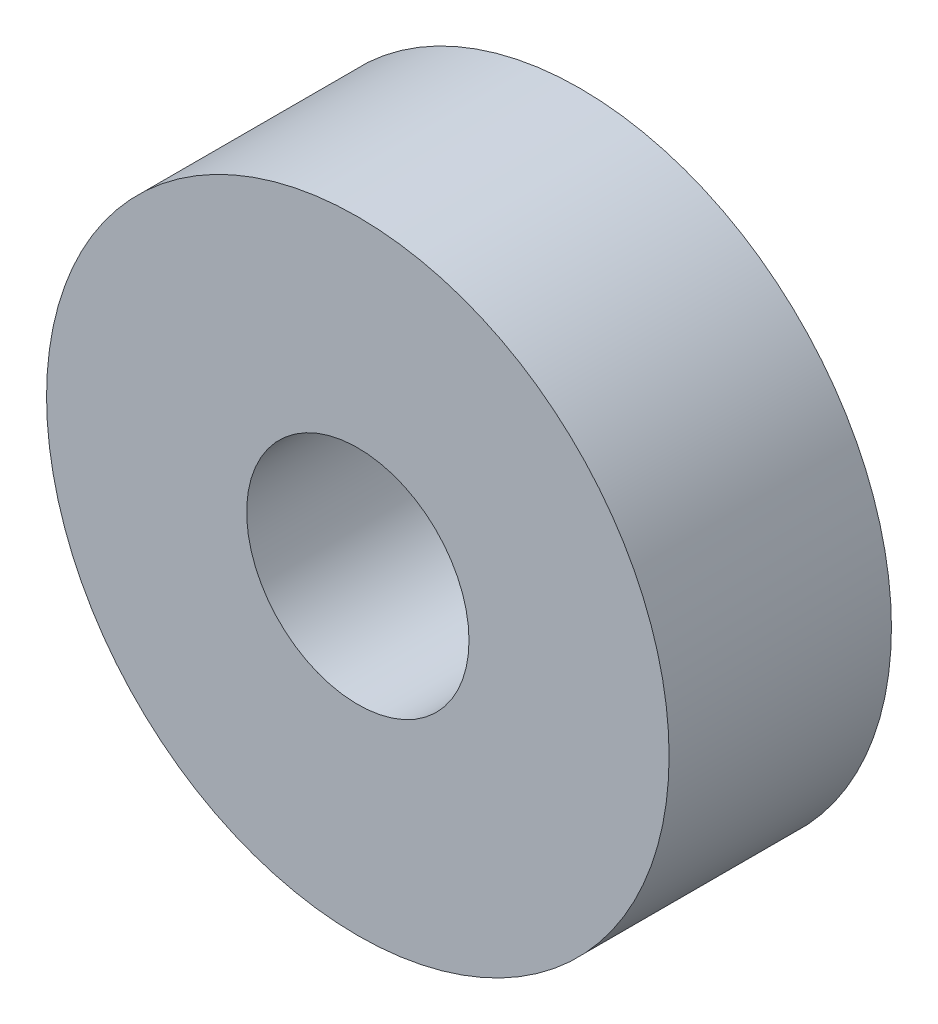
SolidWorks part; units mm, degrees
ref_plane "Спереди" through (0, 0, 0) normal (0, 0, 1) x (1, 0, 0)
ref_plane "Сверху" through (0, 0, 0) normal (0, 1, 0) x (1, 0, 0)
ref_plane "Справа" through (0, 0, 0) normal (1, 0, 0) x (0, 0, -1)
sketch "Эскиз1" plane through (0, 0, 0) normal (0, 0, 1) x (1, 0, 0)
  circle A0 centre (0, 0) radius 7
  circle A1 centre (0, 0) radius 2.5
  dimension "D1" = 5
  dimension "D2" = 14
extrude "Бобышка-Вытянуть1" add sketch "Эскиз1" along normal blind 5
